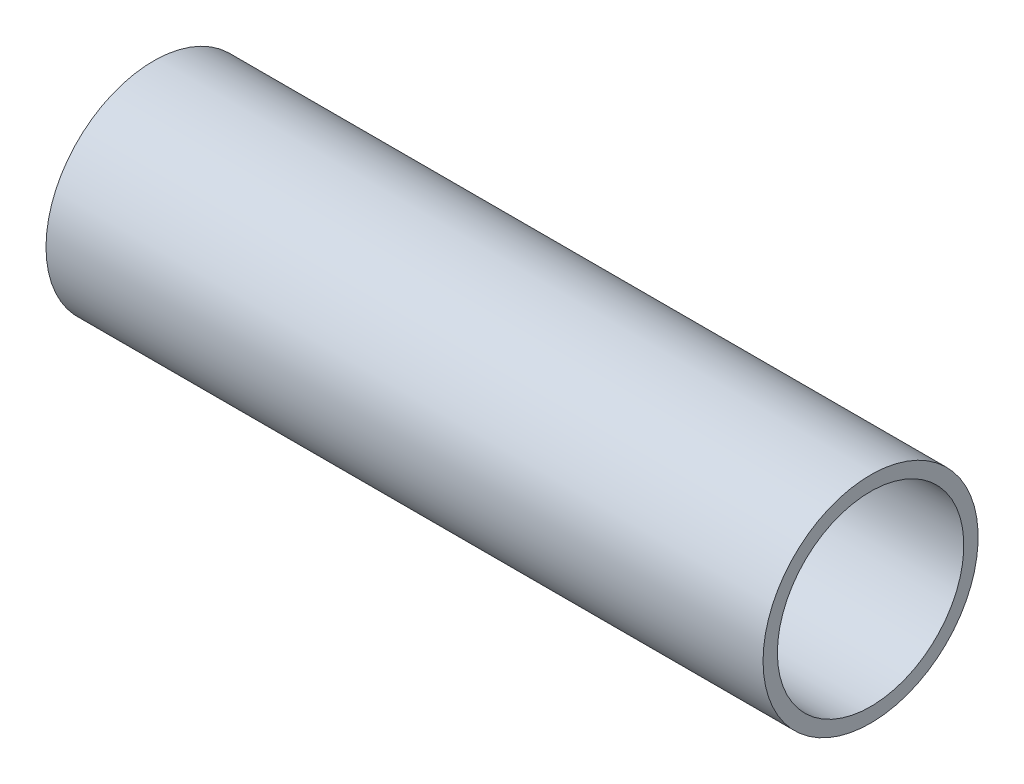
SolidWorks part; units mm, degrees
ref_plane "Plan de face" through (0, 0, 0) normal (0, 0, 1) x (1, 0, 0)
ref_plane "Plan de dessus" through (0, 0, 0) normal (0, 1, 0) x (1, 0, 0)
ref_plane "Plan de droite" through (0, 0, 0) normal (1, 0, 0) x (0, 0, -1)
sketch "Esquisse1" plane through (0, 0, 0) normal (0, 0, 1) x (1, 0, 0)
  line L0 (0, 0) -> (100, 0) construction
  line L2 (0, 15) -> (100, 15)
  line L3 (0, 15) -> (0, 13)
  line L4 (0, 13) -> (100, 13)
  line L5 (100, 15) -> (100, 13)
  dimension "D1" = 100
  dimension "D2" = 2
  dimension "D3" = 15
  dimension "D4" = 100
revolve "Révolution1" add sketch "Esquisse1" angle 360 about L0
